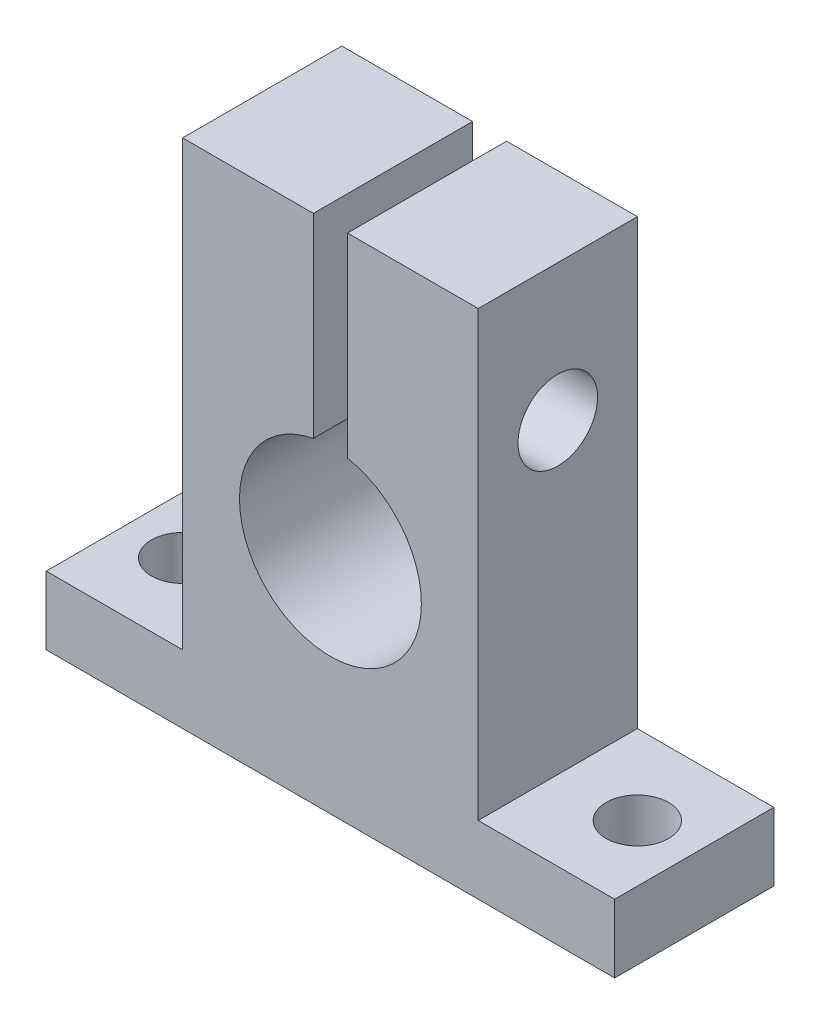
SolidWorks part; units mm, degrees
ref_plane "前视基准面" through (0, 0, 0) normal (0, 0, 1) x (1, 0, 0)
ref_plane "上视基准面" through (0, 0, 0) normal (0, 1, 0) x (1, 0, 0)
ref_plane "右视基准面" through (0, 0, 0) normal (1, 0, 0) x (0, 0, -1)
sketch "草图1" plane through (0, 0, 0) normal (0, 0, 1) x (1, 0, 0)
  line L0 (5.8261, -20.9405) -> (5.8261, -0.9405) construction
  line L1 (-19.1739, 24.0595) -> (30.8261, 24.0595)
  line L2 (-19.1739, 24.0595) -> (-19.1739, -20.9405)
  line L3 (-19.1739, -20.9405) -> (30.8261, -20.9405)
  line L4 (30.8261, 24.0595) -> (30.8261, -20.9405)
  line L5 (30.8261, -14.9405) -> (18.8261, -14.9405)
  line L6 (-19.1739, 24.0595) -> (-7.1739, 24.0595)
  line L7 (-19.1739, 24.0595) -> (-19.1739, -14.9405)
  line L8 (-19.1739, -14.9405) -> (-7.1739, -14.9405)
  line L9 (-7.1739, 24.0595) -> (-7.1739, -14.9405)
  line L10 (18.8261, 24.0595) -> (18.8261, -14.9405)
  line L11 (30.8261, 24.0595) -> (18.8261, 24.0595)
  line L12 (30.8261, 24.0595) -> (30.8261, -14.9405)
  line L13 (5.8261, 24.0595) -> (5.8261, -20.9405) construction
  line L15 (4.3261, 43.6163) -> (7.3261, 43.6163)
  line L16 (4.3261, 43.6163) -> (4.3261, 4.5028)
  line L17 (4.3261, 4.5028) -> (7.3261, 4.5028)
  line L18 (7.3261, 43.6163) -> (7.3261, 4.5028)
  line L19 (4.3261, 43.6163) -> (7.3261, 4.5028) construction
  line L20 (4.3261, 4.5028) -> (7.3261, 43.6163) construction
  circle A0 centre (5.8261, -0.9405) radius 8
  dimension "D4" = 12
  dimension "D1" = 50
  dimension "D2" = 45
  dimension "D3" = 20
  dimension "D5" = 39
  dimension "D6" = 3
extrude "凸台-拉伸1" add sketch "草图1" along normal blind 14 contours A0 L16 L1 L9 L8 L2 L3 L4 L5 L10 L18
sketch "草图2" plane through (18.8261, 0, 0) normal (1, 0, 0) x (0, 0, -1)
  line L0 (-7, 24.0595) -> (-7, 12.0595) construction
  line L1 (-14, 24.0595) -> (0, 24.0595) construction
  circle A0 centre (-7, 12.0595) radius 3.5
  dimension "D1" = 12
extrude "切除-拉伸1" cut sketch "草图2" against normal up to vertex
sketch "草图3" plane through (0, -20.9405, 0) normal (0, -1, 0) x (-1, 0, 0)
  line L0 (19.1739, -7) -> (14.1739, -7) construction
  line L1 (19.1739, -14) -> (19.1739, 0) construction
  line L2 (-5.8261, -14) -> (-5.8261, 0) construction
  line L3 (19.1739, -14) -> (-30.8261, -14) construction
  line L4 (19.1739, 0) -> (-30.8261, 0) construction
  circle A0 centre (14.1739, -7) radius 2.75
  circle A1 centre (-25.8261, -7) radius 2.75
  dimension "D1" = 5
extrude "切除-拉伸2" cut sketch "草图3" against normal blind 14
